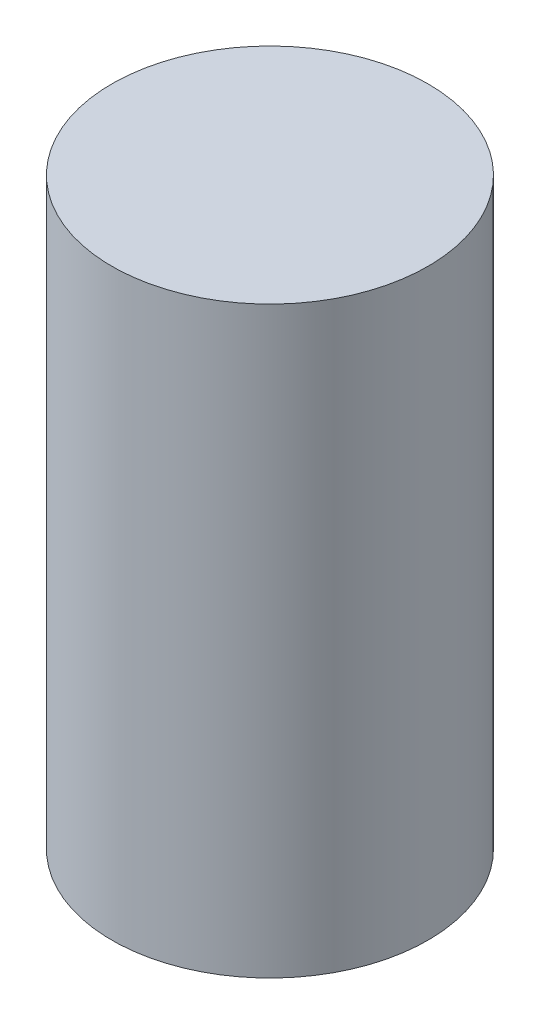
SolidWorks part; units mm, degrees
material "Copper"
ref_plane "Front Plane" through (0, 0, 0) normal (0, 0, 1) x (1, 0, 0)
ref_plane "Top Plane" through (0, 0, 0) normal (0, 1, 0) x (1, 0, 0)
ref_plane "Right Plane" through (0, 0, 0) normal (1, 0, 0) x (0, 0, -1)
sketch "Sketch1" plane through (0, 0, 0) normal (0, 1, 0) x (1, 0, 0)
  circle A0 centre (0, 0) radius 20.6375
extrude "Boss-Extrude1" add sketch "Sketch1" along normal blind 76.2
